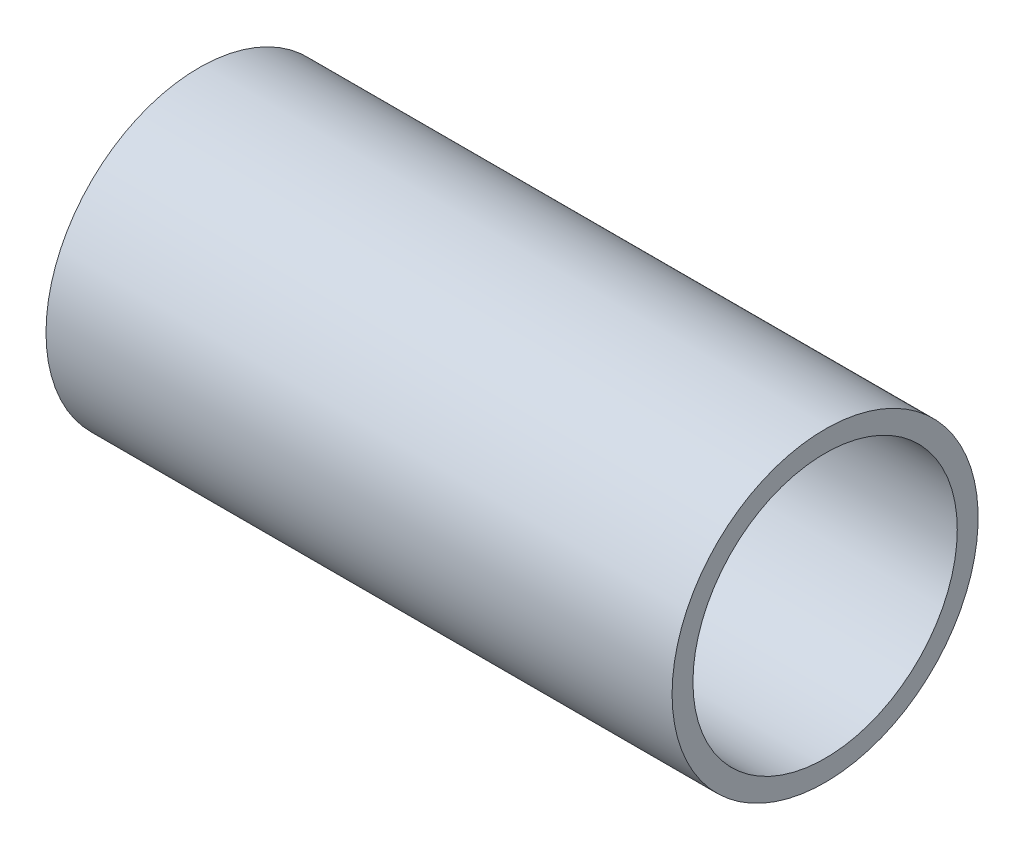
SolidWorks part; units mm, degrees
material "PVC 0.007 Plasticized"
ref_plane "Front Plane" through (0, 0, 0) normal (0, 0, 1) x (1, 0, 0)
ref_plane "Top Plane" through (0, 0, 0) normal (0, 1, 0) x (1, 0, 0)
ref_plane "Right Plane" through (0, 0, 0) normal (1, 0, 0) x (0, 0, -1)
sketch "Sketch1" plane through (0, 0, 0) normal (1, 0, 0) x (0, 0, -1)
  circle A0 centre (0, 0) radius 11
  circle A1 centre (0, 0) radius 9.5
  dimension "D1" = 1.5
extrude "Boss-Extrude1" add sketch "Sketch1" along normal blind 45
